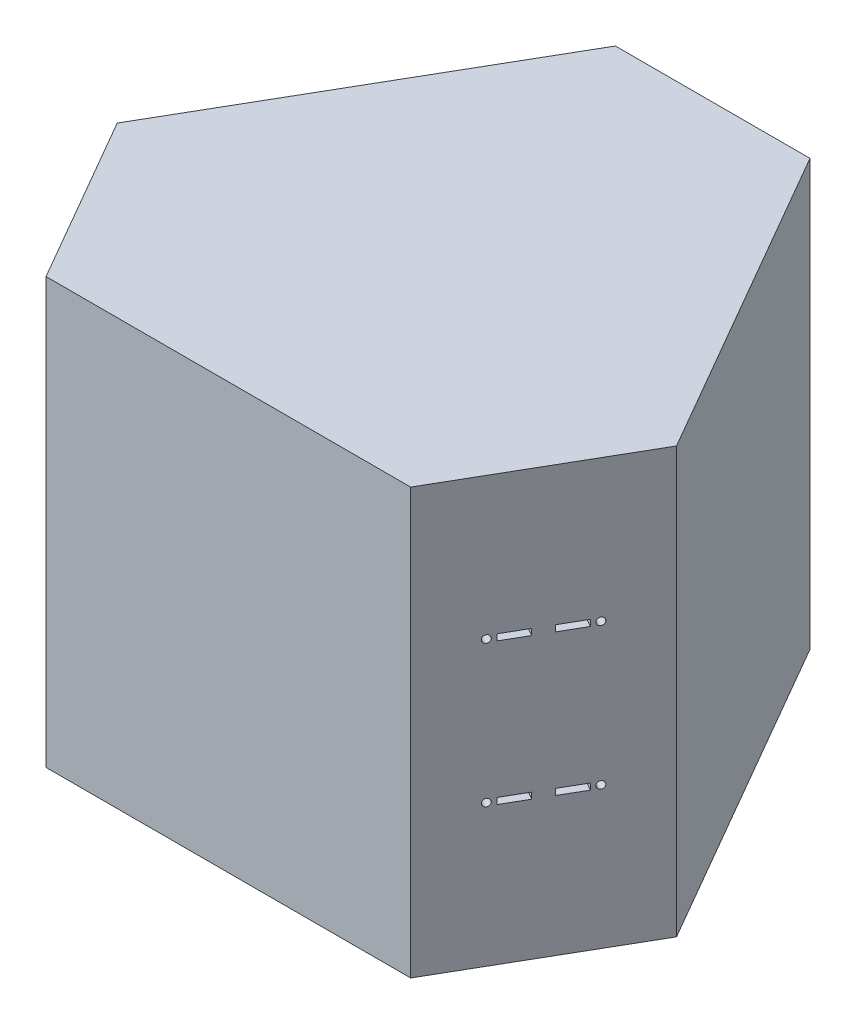
SolidWorks part; units mm, degrees
ref_plane "Front Plane" through (0, 0, 0) normal (0, 0, 1) x (1, 0, 0)
ref_plane "Top Plane" through (0, 0, 0) normal (0, 1, 0) x (1, 0, 0)
ref_plane "Right Plane" through (0, 0, 0) normal (1, 0, 0) x (0, 0, -1)
sketch "Sketch1" plane through (0, 0, 0) normal (0, 1, 0) x (1, 0, 0)
  line L0 (50.8, 0) -> (-50.8, 0)
  line L7 (-50.8, 0) -> (-76.2, 43.9941)
  line L8 (-76.2, 43.9941) -> (-25.4, 131.9823)
  line L9 (-25.4, 131.9823) -> (25.4, 131.9823)
  line L10 (25.4, 131.9823) -> (76.2, 43.9941)
  line L11 (76.2, 43.9941) -> (50.8, 0)
  line L12 (54.4662, -6.35) -> (-54.4662, -6.35)
  line L13 (-54.4662, -6.35) -> (-83.5323, 43.9941)
  line L14 (-83.5323, 43.9941) -> (-29.0662, 138.3323)
  line L15 (-29.0662, 138.3323) -> (29.0662, 138.3323)
  line L16 (29.0662, 138.3323) -> (83.5323, 43.9941)
  line L17 (83.5323, 43.9941) -> (54.4662, -6.35)
  point P3 (0, 0)
  dimension "D1" = 101.6
  dimension "D2" = 120
  dimension "D3" = 6.35
extrude "Boss-Extrude1" add sketch "Sketch1" along normal blind 120.65
sketch "Sketch2" plane through (0, 120.65, 0) normal (0, 1, 0) x (1, 0, 0)
  line L0 (-29.0662, 138.3323) -> (-83.5323, 43.9941)
  line L1 (-83.5323, 43.9941) -> (-54.4662, -6.35)
  line L2 (-54.4662, -6.35) -> (54.4662, -6.35)
  line L3 (54.4662, -6.35) -> (83.5323, 43.9941)
  line L4 (83.5323, 43.9941) -> (29.0662, 138.3323)
  line L5 (83.5323, 43.9941) -> (29.0662, 138.3323) construction
  line L6 (29.0662, 138.3323) -> (-29.0662, 138.3323) construction
  line L7 (29.0662, 138.3323) -> (-29.0662, 138.3323)
extrude "Boss-Extrude2" add sketch "Sketch2" along normal blind 6.35
sketch "Sketch3" plane through (-43.5993, 0, 25.172) normal (-0.866, 0, 0.5) x (0.5, 0, 0.866)
  line L0 (-79.8662, 63.5) -> (-21.7338, 63.5) construction
  line L5 (-53.4, 85.5874) -> (-53.4, 83.7459)
  line L6 (-53.4, 85.5874) -> (-61.02, 85.5874)
  line L7 (-53.4, 83.7459) -> (-61.02, 83.7459)
  line L16 (-61.02, 85.5874) -> (-61.02, 83.7459)
  line L17 (-48.2, 83.7459) -> (-40.58, 83.7459)
  line L18 (-40.58, 85.5874) -> (-40.58, 83.7459)
  line L19 (-48.2, 85.5874) -> (-40.58, 85.5874)
  line L20 (-48.2, 85.5874) -> (-48.2, 83.7459)
  line L21 (-39.1764, 44.5241) -> (-62.4236, 44.5241)
  line L22 (-62.4236, 86.8574) -> (-39.1764, 86.8574)
  line L23 (-39.1764, 82.4759) -> (-62.4236, 82.4759)
  line L24 (-62.4236, 40.1426) -> (-39.1764, 40.1426)
  line L25 (-48.2, 41.4126) -> (-48.2, 43.2541)
  line L26 (-48.2, 41.4126) -> (-40.58, 41.4126)
  line L27 (-40.58, 41.4126) -> (-40.58, 43.2541)
  line L28 (-48.2, 43.2541) -> (-40.58, 43.2541)
  line L29 (-61.02, 41.4126) -> (-61.02, 43.2541)
  line L30 (-53.4, 43.2541) -> (-61.02, 43.2541)
  line L31 (-53.4, 41.4126) -> (-61.02, 41.4126)
  line L32 (-53.4, 41.4126) -> (-53.4, 43.2541)
  circle A1 centre (-38.2799, 84.6667) radius 1.0954
  circle A2 centre (-63.3201, 84.6667) radius 1.0954
  arc A4 (-62.4236, 86.8574) -> (-62.4236, 82.4759) centre (-63.3201, 84.6667) ccw
  arc A5 (-39.1764, 86.8574) -> (-39.1764, 82.4759) centre (-38.2799, 84.6667) cw
  arc A6 (-39.1764, 40.1426) -> (-39.1764, 44.5241) centre (-38.2799, 42.3333) ccw
  arc A7 (-62.4236, 40.1426) -> (-62.4236, 44.5241) centre (-63.3201, 42.3333) cw
  circle A8 centre (-63.3201, 42.3333) radius 1.0954
  circle A9 centre (-38.2799, 42.3333) radius 1.0954
  point P8 (-50.8, 84.6667)
  point P9 (-50.8, 84.6667)
  point P13 (-50.8, 84.6667)
  point P17 (-50.8, 84.6667)
  point P32 (-62.4236, 86.8574)
  point P33 (-37.3835, 86.8574)
  point P34 (-62.4236, 82.4759)
  point P35 (-37.3835, 86.8574)
  point P36 (-39.1764, 86.8574)
  point P37 (-39.1764, 82.4759)
  point P38 (-39.1764, 82.4759)
  point P39 (-39.1764, 82.4759)
  point P48 (-39.1764, 44.5241)
  point P49 (-39.1764, 44.5241)
  point P50 (-39.1764, 44.5241)
  point P51 (-39.1764, 40.1426)
  point P52 (-37.3835, 40.1426)
  point P53 (-62.4236, 44.5241)
  point P54 (-62.4236, 40.1426)
  point P55 (-50.8, 42.3333)
  dimension "D5" = 2.1907
  dimension "D2" = 7.62
extrude "Cut-Extrude1" cut sketch "Sketch3" against normal up to surface (221.8171 mm away) contours L6 L16 L7 L5 | A2 | A1 | L19 L20 L17 L18 | L29 L30 L32 L31 | L25 L28 L27 L26 | A8 | A9
sketch "Sketch5" plane through (0, 0, 0) normal (0, -1, 0) x (1, 0, 0)
  point P17 (0, -58.6588)
sketch "Sketch6" plane through (0, 0, 0) normal (1, 0, 0) x (0, 0, -1)
  line L0 (58.6588, 0) -> (58.6588, 127) construction
  line L1 (43.9941, 127) -> (138.3323, 127) construction
pattern_circular "CirPattern1" count 3 over 360 about axis through (0, 0, -58.6588) along (0, 1, 0) of "Cut-Extrude1"
sketch "Sketch7" plane through (-81.6993, 0, -47.1691) normal (-0.866, 0, -0.5) x (-0.5, 0, 0.866)
  line L1 (-79.5339, 101.4603) -> (-25.0742, 101.4603)
  line L2 (-79.5339, 101.4603) -> (-79.5339, 27.6166)
  line L3 (-79.5339, 27.6166) -> (-25.0742, 27.6166)
  line L4 (-25.0742, 101.4603) -> (-25.0742, 27.6166)
  point P4 (-25.0742, 27.6166)
extrude "Boss-Extrude3" add sketch "Sketch7" against normal up to surface (6.35 mm away)
sketch "Sketch8" plane through (0, 0, 6.35) normal (0, 0, 1) x (1, 0, 0)
  line L1 (-32.122, 97.0066) -> (25.8453, 97.0066)
  line L2 (-32.122, 97.0066) -> (-32.122, 31.6549)
  line L3 (-32.122, 31.6549) -> (25.8453, 31.6549)
  line L4 (25.8453, 97.0066) -> (25.8453, 31.6549)
extrude "Boss-Extrude4" add sketch "Sketch8" against normal up to surface (6.35 mm away)
